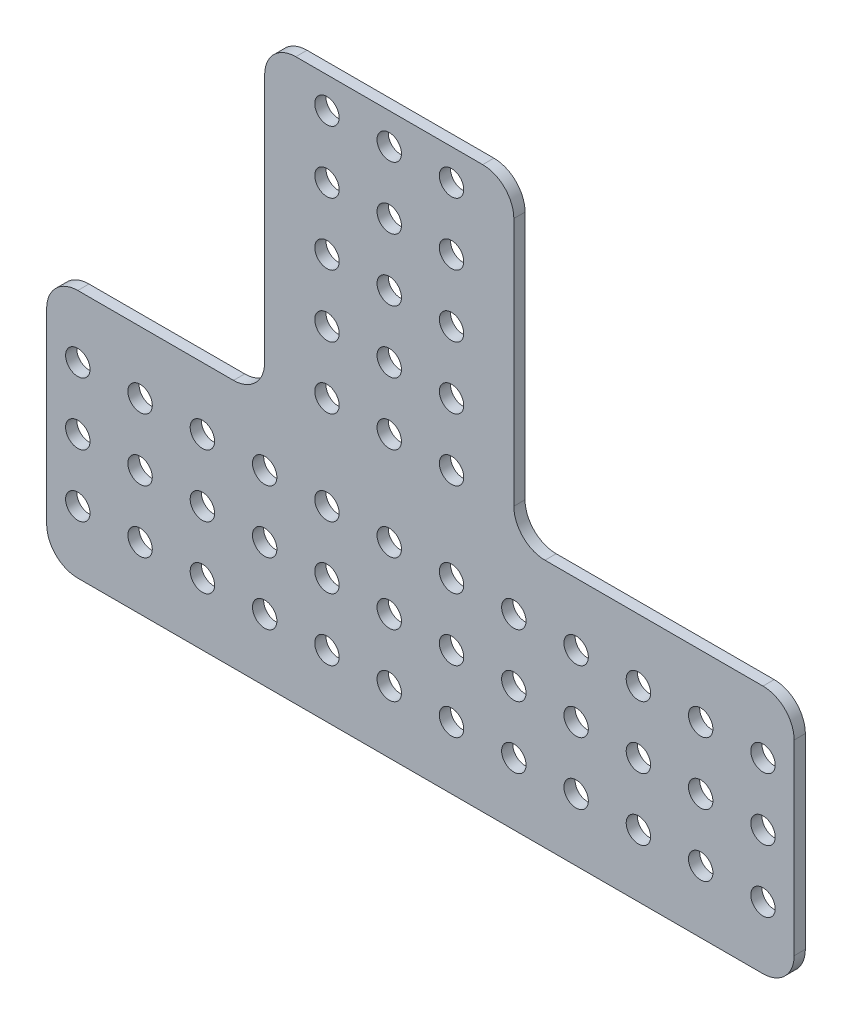
SolidWorks part; units mm, degrees
ref_plane "Front Plane" through (0, 0, 0) normal (0, 0, 1) x (1, 0, 0)
ref_plane "Top Plane" through (0, 0, 0) normal (0, 1, 0) x (1, 0, 0)
ref_plane "Right Plane" through (0, 0, 0) normal (1, 0, 0) x (0, 0, -1)
sketch "Sketch1" plane through (0, 0, 0) normal (0, 0, 1) x (1, 0, 0)
  line L0 (-258.2184, 188.8429) -> (-220.1184, 188.8429)
  line L1 (-213.7684, 182.4929) -> (-213.7684, 131.6929)
  line L2 (-207.4184, 125.3429) -> (-162.9684, 125.3429)
  line L3 (-156.6184, 118.9929) -> (-156.6184, 80.8929)
  line L4 (-162.9684, 74.5429) -> (-302.6684, 74.5429)
  line L5 (-309.0184, 80.8929) -> (-309.0184, 118.9929)
  line L6 (-302.6684, 125.3429) -> (-270.9184, 125.3429)
  line L8 (-264.5684, 125.3429) -> (-213.7684, 125.3429) construction
  line L9 (-213.7684, 811.1429) -> (-213.7684, 125.3429) construction
  line L10 (-302.6684, 112.6429) -> (-289.9684, 112.6429) construction
  line L11 (-302.6684, 112.6429) -> (-302.6684, 99.9429) construction
  line L12 (-226.4684, 131.6929) -> (-226.4684, 112.6429) construction
  line L13 (-264.5684, 131.6929) -> (-264.5684, 182.4929)
  arc A0 (-270.9184, 125.3429) -> (-264.5684, 131.6929) centre (-270.9184, 131.6929) ccw
  arc A1 (-309.0184, 118.9929) -> (-302.6684, 125.3429) centre (-302.6684, 118.9929) cw
  arc A2 (-302.6684, 74.5429) -> (-309.0184, 80.8929) centre (-302.6684, 80.8929) cw
  arc A3 (-156.6184, 80.8929) -> (-162.9684, 74.5429) centre (-162.9684, 80.8929) cw
  arc A4 (-162.9684, 125.3429) -> (-156.6184, 118.9929) centre (-162.9684, 118.9929) cw
  arc A5 (-213.7684, 131.6929) -> (-207.4184, 125.3429) centre (-207.4184, 131.6929) ccw
  arc A7 (-220.1184, 188.8429) -> (-213.7684, 182.4929) centre (-220.1184, 182.4929) cw
  circle A8 centre (-226.4684, 182.4929) radius 2.4892 construction
  circle A9 centre (-226.4684, 157.0929) radius 2.4892 construction
  circle A10 centre (-226.4684, 144.3929) radius 2.4892 construction
  circle A11 centre (-226.4684, 131.6929) radius 2.4892 construction
  circle A12 centre (-239.1684, 131.6929) radius 2.4892 construction
  circle A13 centre (-251.8684, 131.6929) radius 2.4892 construction
  circle A14 centre (-251.8684, 144.3929) radius 2.4892 construction
  circle A15 centre (-239.1684, 144.3929) radius 2.4892 construction
  circle A16 centre (-239.1684, 157.0929) radius 2.4892 construction
  circle A17 centre (-251.8684, 157.0929) radius 2.4892 construction
  circle A18 centre (-226.4684, 169.7929) radius 2.4892 construction
  circle A19 centre (-239.1684, 182.4929) radius 2.4892 construction
  circle A20 centre (-239.1684, 169.7929) radius 2.4892 construction
  circle A21 centre (-251.8684, 169.7929) radius 2.4892 construction
  circle A22 centre (-251.8684, 182.4929) radius 2.4892 construction
  circle A23 centre (-226.4684, 157.0929) radius 2.4892
  circle A24 centre (-226.4684, 144.3929) radius 2.4892
  circle A25 centre (-226.4684, 131.6929) radius 2.4892
  circle A26 centre (-239.1684, 131.6929) radius 2.4892
  circle A27 centre (-251.8684, 131.6929) radius 2.4892
  circle A28 centre (-251.8684, 144.3929) radius 2.4892
  circle A29 centre (-239.1684, 144.3929) radius 2.4892
  circle A30 centre (-239.1684, 157.0929) radius 2.4892
  circle A31 centre (-251.8684, 157.0929) radius 2.4892
  circle A32 centre (-226.4684, 169.7929) radius 2.4892
  circle A33 centre (-226.4684, 182.4929) radius 2.4892
  circle A34 centre (-239.1684, 182.4929) radius 2.4892
  circle A35 centre (-239.1684, 169.7929) radius 2.4892
  circle A36 centre (-251.8684, 169.7929) radius 2.4892
  circle A37 centre (-251.8684, 182.4929) radius 2.4892
  circle A38 centre (-302.6684, 112.6429) radius 2.4892
  circle A39 centre (-289.9684, 112.6429) radius 2.4892
  circle A40 centre (-277.2684, 112.6429) radius 2.4892
  circle A41 centre (-264.5684, 112.6429) radius 2.4892
  circle A42 centre (-251.8684, 112.6429) radius 2.4892
  circle A43 centre (-239.1684, 112.6429) radius 2.4892
  circle A44 centre (-226.4684, 112.6429) radius 2.4892
  circle A45 centre (-213.7684, 112.6429) radius 2.4892
  circle A46 centre (-201.0684, 112.6429) radius 2.4892
  circle A47 centre (-188.3684, 112.6429) radius 2.4892
  circle A48 centre (-175.6684, 112.6429) radius 2.4892
  circle A49 centre (-162.9684, 112.6429) radius 2.4892
  circle A50 centre (-289.9684, 99.9429) radius 2.4892
  circle A51 centre (-277.2684, 99.9429) radius 2.4892
  circle A52 centre (-264.5684, 99.9429) radius 2.4892
  circle A53 centre (-251.8684, 99.9429) radius 2.4892
  circle A54 centre (-239.1684, 99.9429) radius 2.4892
  circle A55 centre (-226.4684, 99.9429) radius 2.4892
  circle A56 centre (-213.7684, 99.9429) radius 2.4892
  circle A57 centre (-201.0684, 99.9429) radius 2.4892
  circle A58 centre (-188.3684, 99.9429) radius 2.4892
  circle A59 centre (-175.6684, 99.9429) radius 2.4892
  circle A60 centre (-162.9684, 99.9429) radius 2.4892
  circle A61 centre (-289.9684, 87.2429) radius 2.4892
  circle A62 centre (-277.2684, 87.2429) radius 2.4892
  circle A63 centre (-264.5684, 87.2429) radius 2.4892
  circle A64 centre (-251.8684, 87.2429) radius 2.4892
  circle A65 centre (-239.1684, 87.2429) radius 2.4892
  circle A66 centre (-226.4684, 87.2429) radius 2.4892
  circle A67 centre (-213.7684, 87.2429) radius 2.4892
  circle A68 centre (-201.0684, 87.2429) radius 2.4892
  circle A69 centre (-188.3684, 87.2429) radius 2.4892
  circle A70 centre (-175.6684, 87.2429) radius 2.4892
  circle A71 centre (-162.9684, 87.2429) radius 2.4892
  circle A72 centre (-302.6684, 99.9429) radius 2.4892
  circle A73 centre (-302.6684, 87.2429) radius 2.4892
  arc A75 (-264.5684, 182.4929) -> (-258.2184, 188.8429) centre (-258.2184, 182.4929) cw
  dimension "D2" = 6.35
  dimension "D6" = 12.7
  dimension "D8" = 4.9784
  dimension "D9" = 12
  dimension "D4" = 6.35
  dimension "D1" = 6.35
  dimension "D3" = 152.4
  dimension "D5" = 50.8
  dimension "D7" = 50.8
  dimension "D11" = 12.7
  dimension "D12" = 12.7
  dimension "D10" = 3
extrude "Boss-Extrude1" add sketch "Sketch1" along normal blind 2.286
